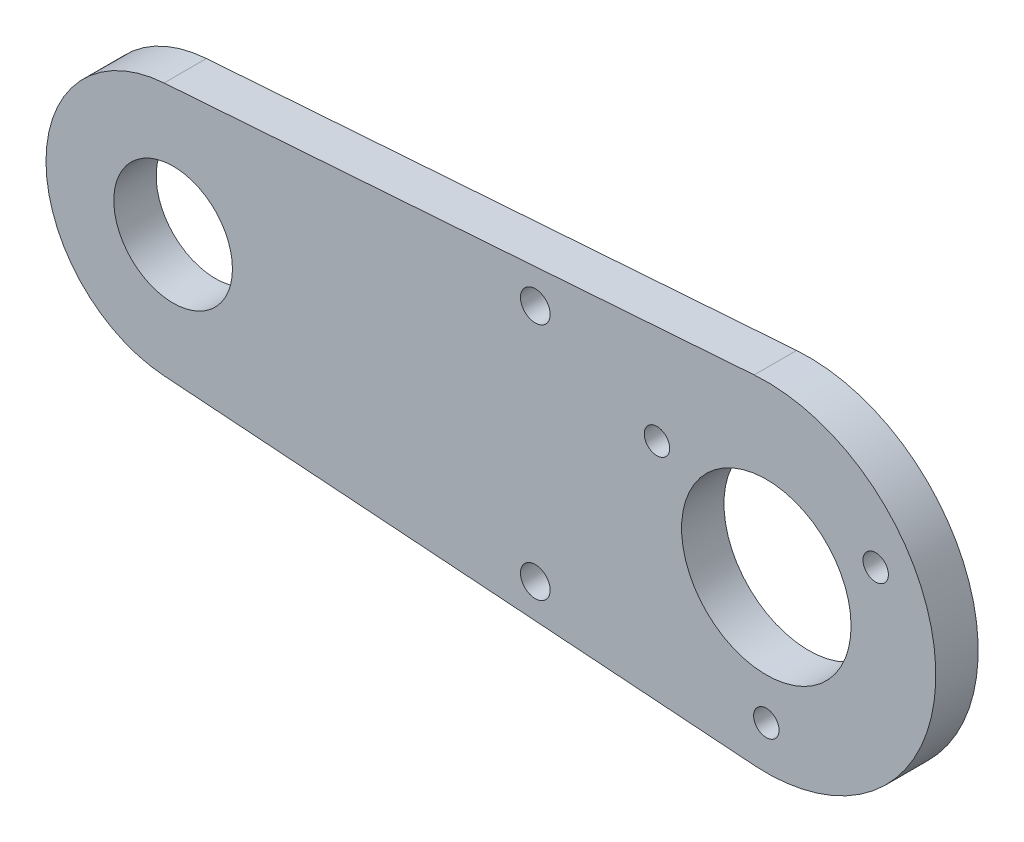
SolidWorks part; units mm, degrees
ref_plane "Front Plane" through (0, 0, 0) normal (0, 0, 1) x (1, 0, 0)
ref_plane "Top Plane" through (0, 0, 0) normal (0, 1, 0) x (1, 0, 0)
ref_plane "Right Plane" through (0, 0, 0) normal (1, 0, 0) x (0, 0, -1)
sketch "Sketch1" plane through (0, 0, 0) normal (0, 0, 1) x (1, 0, 0)
  line L0 (-71.0714, 14.9617) -> (-1.4286, 19.9489)
  line L1 (-71.0714, -14.9617) -> (-1.4286, -19.9489)
  arc A0 (-1.4286, -19.9489) -> (-1.4286, 19.9489) centre (0, 0) ccw
  arc A1 (-71.0714, -14.9617) -> (-71.0714, 14.9617) centre (-70, 0) cw
  circle A3 centre (-70, 0) radius 7
  circle A4 centre (0, 0) radius 10
  circle A5 centre (-12.9038, 7.45) radius 1.5
  circle A6 centre (0, -14.9) radius 1.5
  circle A16 centre (-27.2623, 14.0887) radius 1.75
  circle A17 centre (-27.2623, -14.0887) radius 1.75
  circle A18 centre (12.9038, 7.45) radius 1.5
  point P9 (-85, 0)
  dimension "D2" = 20
  dimension "D3" = 15
  dimension "D6" = 3
  dimension "D7" = 14
  dimension "D10" = 3.5
  dimension "D13" = 3.5
  dimension "D5" = 3
  dimension "D4" = 20
  dimension "D9" = 3
  dimension "D1" = 70
  dimension "D8" = 15
  dimension "D11" = 4
  dimension "D12" = 45
  dimension "D14" = 4
  dimension "D15" = 45
extrude "Boss-Extrude1" add sketch "Sketch1" along normal blind 5
